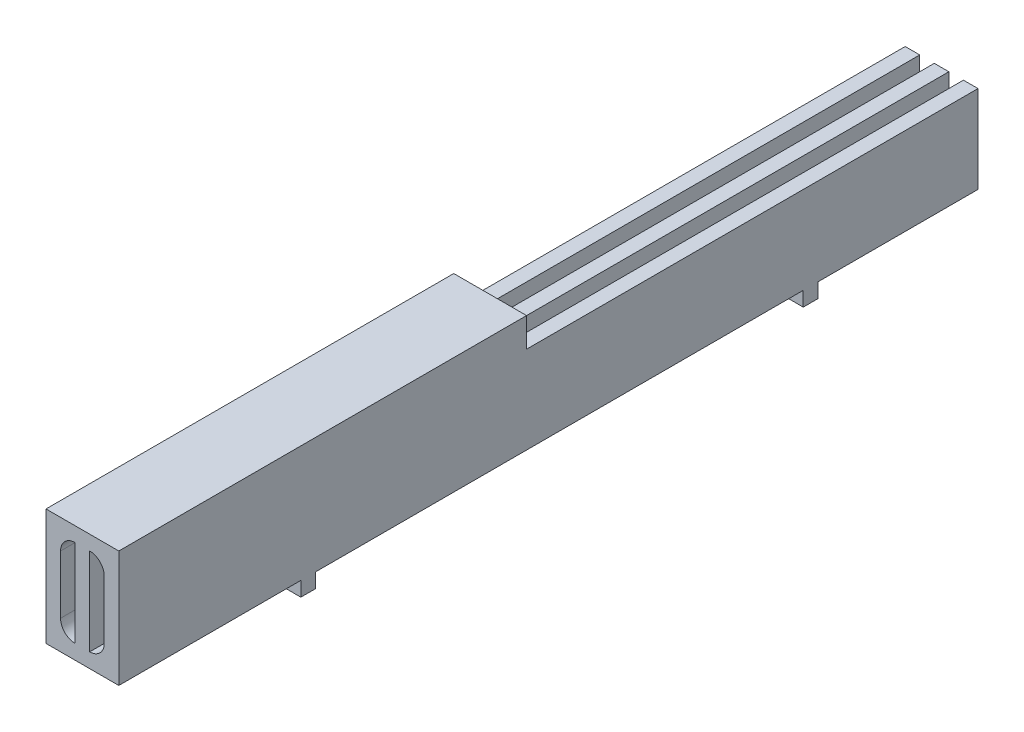
SolidWorks part; units mm, degrees
ref_plane "Front Plane" through (0, 0, 0) normal (0, 0, 1) x (1, 0, 0)
ref_plane "Top Plane" through (0, 0, 0) normal (0, 1, 0) x (1, 0, 0)
ref_plane "Right Plane" through (0, 0, 0) normal (1, 0, 0) x (0, 0, -1)
sketch "Sketch1" plane through (0, 0, 0) normal (0, 0, 1) x (1, 0, 0)
  line L1 (-2.5, 4) -> (2.5, 4)
  line L2 (-2.5, 4) -> (-2.5, -4)
  line L3 (-2.5, -4) -> (2.5, -4)
  line L4 (2.5, 4) -> (2.5, -4)
  line L5 (-2.5, 4) -> (2.5, -4) construction
  line L6 (-2.5, -4) -> (2.5, 4) construction
  line L7 (-0.5, 3) -> (0.5, 3)
  line L8 (-1.5, 2) -> (-1.5, -2)
  line L9 (-0.5, -3) -> (0.5, -3)
  line L10 (1.5, 2) -> (1.5, -2)
  line L11 (-1.5, 3) -> (1.5, -3) construction
  line L12 (-1.5, -3) -> (1.5, 3) construction
  line L13 (-0.5, 3) -> (0.5, 3)
  line L14 (-0.5, 3) -> (-0.5, -3)
  line L15 (-0.5, -3) -> (0.5, -3)
  line L16 (0.5, 3) -> (0.5, -3)
  line L17 (-0.5, 3) -> (0.5, -3) construction
  line L18 (-0.5, -3) -> (0.5, 3) construction
  arc A0 (-0.5, 3) -> (-1.5, 2) centre (-0.5, 2) ccw
  arc A1 (-0.5, -3) -> (-1.5, -2) centre (-0.5, -2) cw
  arc A2 (1.5, -2) -> (0.5, -3) centre (0.5, -2) cw
  arc A3 (1.5, 2) -> (0.5, 3) centre (0.5, 2) ccw
  point P0 (0, 0)
  point P6 (0, 0)
  point P11 (0, 0)
  dimension "D6" = 1
  dimension "D7" = 1
  dimension "D1" = 5
  dimension "D2" = 8
  dimension "D3" = 1
  dimension "D4" = 1
  dimension "D5" = 1
extrude "Boss-Extrude3" add sketch "Sketch1" along normal blind 59 contours L4 L1 L2 L3 L7 L10 L9 L8 | L16 L7 L14 L9
sketch "Sketch6" plane through (0, 4, 0) normal (0, 1, 0) x (1, 0, 0)
  line L0 (-2.5, -59) -> (-2.5, 0) construction
  line L1 (-2.5, -31) -> (2.5, -31)
  line L2 (-2.5, -31) -> (-2.5, 0)
  line L3 (-2.5, 0) -> (2.5, 0)
  line L4 (2.5, -31) -> (2.5, 0)
  line L5 (2.5, -59) -> (2.5, 0) construction
  line L6 (-2.5, -59) -> (2.5, -59) construction
  line L11 (-2.5, 0) -> (2.5, 0) construction
  dimension "D1" = 28
sketch "Sketch8" plane through (0, -4, 0) normal (0, -1, 0) x (1, 0, 0)
  line L0 (2.5, 12) -> (-2.5, 12)
  line L1 (2.5, 59) -> (2.5, 0) construction
  line L2 (-2.5, 59) -> (-2.5, 0) construction
  line L3 (-2.5, 59) -> (2.5, 59) construction
  line L4 (2.5, 12) -> (2.5, 11)
  line L5 (2.5, 11) -> (-2.5, 11)
  line L6 (-2.5, 11) -> (-2.5, 12)
  dimension "D1" = 47
  dimension "D2" = 1
extrude "Boss-Extrude5" add sketch "Sketch8" along normal blind 1
sketch "Sketch9" plane through (0, 0, 0) normal (0, 0, -1) x (-1, 0, 0)
  line L0 (-1.5, 2) -> (1.5, 2) construction
  line L1 (-2.5, 2) -> (2.5, 2)
  line L2 (-2.5, 2) -> (-2.5, -4)
  line L3 (-2.5, -4) -> (2.5, -4)
  line L4 (2.5, 2) -> (2.5, -4)
  dimension "D1" = 5
sketch "Sketch10" plane through (0, -4, 0) normal (0, -1, 0) x (1, 0, 0)
  line L0 (-2.5, 46.5) -> (2.5, 46.5)
  line L1 (-2.5, 59) -> (-2.5, 12) construction
  line L2 (2.5, 59) -> (2.5, 12) construction
  line L3 (-2.5, 59) -> (2.5, 59) construction
  line L4 (-2.5, 46.5) -> (-2.5, 45.5)
  line L5 (-2.5, 45.5) -> (2.5, 45.5)
  line L6 (2.5, 45.5) -> (2.5, 46.5)
  dimension "D1" = 12.5
  dimension "D2" = 1
extrude "Boss-Extrude7" add sketch "Sketch10" along normal blind 1
extrude "Cut-Extrude1" cut sketch "Sketch6" against normal blind 2
